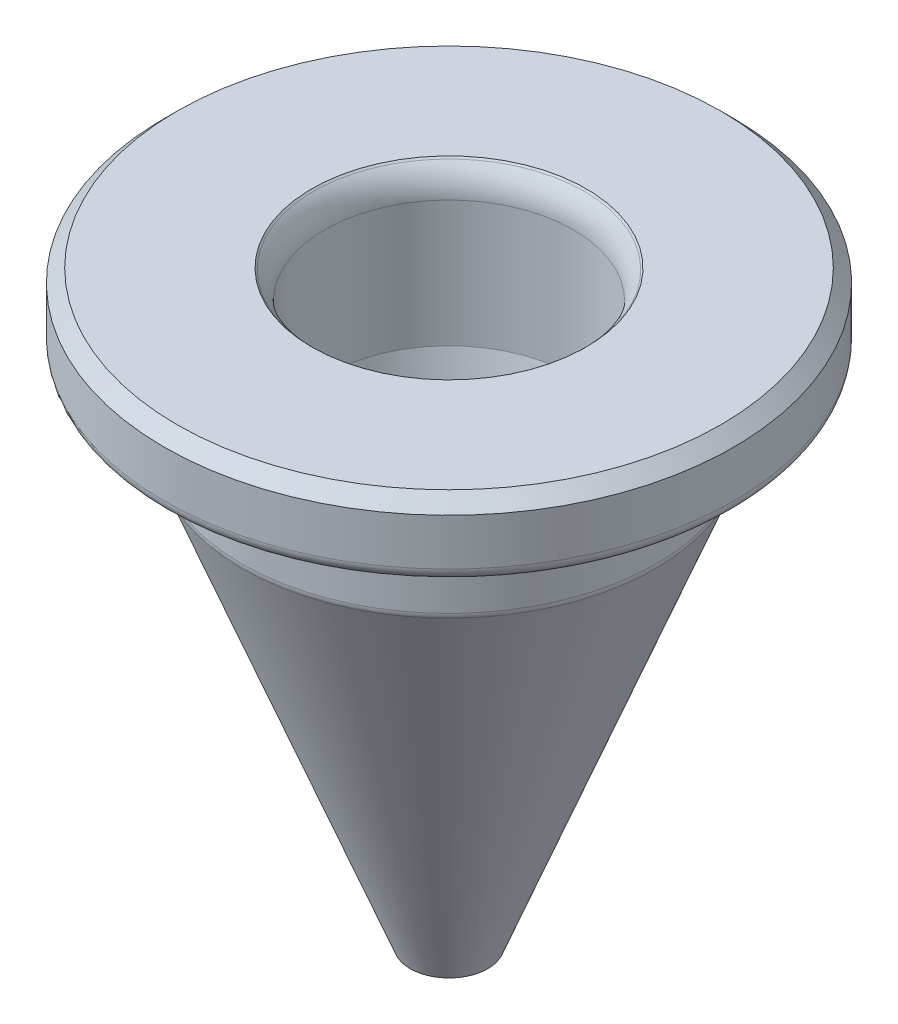
SolidWorks part; units mm, degrees
ref_plane "Ebene vorne" through (0, 0, 0) normal (0, 0, 1) x (1, 0, 0)
ref_plane "Ebene oben" through (0, 0, 0) normal (0, 1, 0) x (1, 0, 0)
ref_plane "Ebene rechts" through (0, 0, 0) normal (1, 0, 0) x (0, 0, -1)
sketch "Skizze1" plane through (0, 0, 0) normal (0, 0, 1) x (1, 0, 0)
  line L0 (0, 0) -> (0, 22) construction
  line L1 (1, 0) -> (4.8, 17)
  line L2 (4.8, 17) -> (4.8, 22)
  line L3 (4.8, 22) -> (8, 22)
  line L5 (8, 22) -> (8, 17)
  line L7 (1, 0) -> (1.5, 0.3)
  line L8 (1.5, 0.3) -> (8, 17)
  dimension "D1" = 9.6
  dimension "D2" = 22
  dimension "D3" = 5
  dimension "D4" = 2
  dimension "D5" = 16
  dimension "D6" = 0.5
  dimension "D7" = 0.3
revolve "Rotation1" add sketch "Skizze1" angle 360 about L0
other "Fläche verschieben1" face at (0, 22, -4.8) parameters "D1"=1
sketch "Skizze2" plane through (0, 23, 0) normal (0, 1, 0) x (1, 0, 0)
  circle A0 centre (0, 0) radius 11
  circle A3 centre (0, 0) radius 4.8 construction
  circle A4 centre (0, 0) radius 4.8
  dimension "D1" = 22
extrude "Aufsatz-Linear austragen1" add sketch "Skizze2" against normal blind 2.8
fillet "Verrundung1" radius 0.5 3 edges at (0, 17, -8) (0, 20.2, 11) (0, 20.2, 8)
ref_plane "Ebene1" through (0, 0, 0) normal (0, 0, 1) x (1, 0, 0)
chamfer "Fase1" distance 0.5 angle 45 2 edges at (0, 23, 11) (0, 23, 4.8)
fillet "Verrundung2" radius 1.5 1 edges at (0, 22.5, 4.8)
